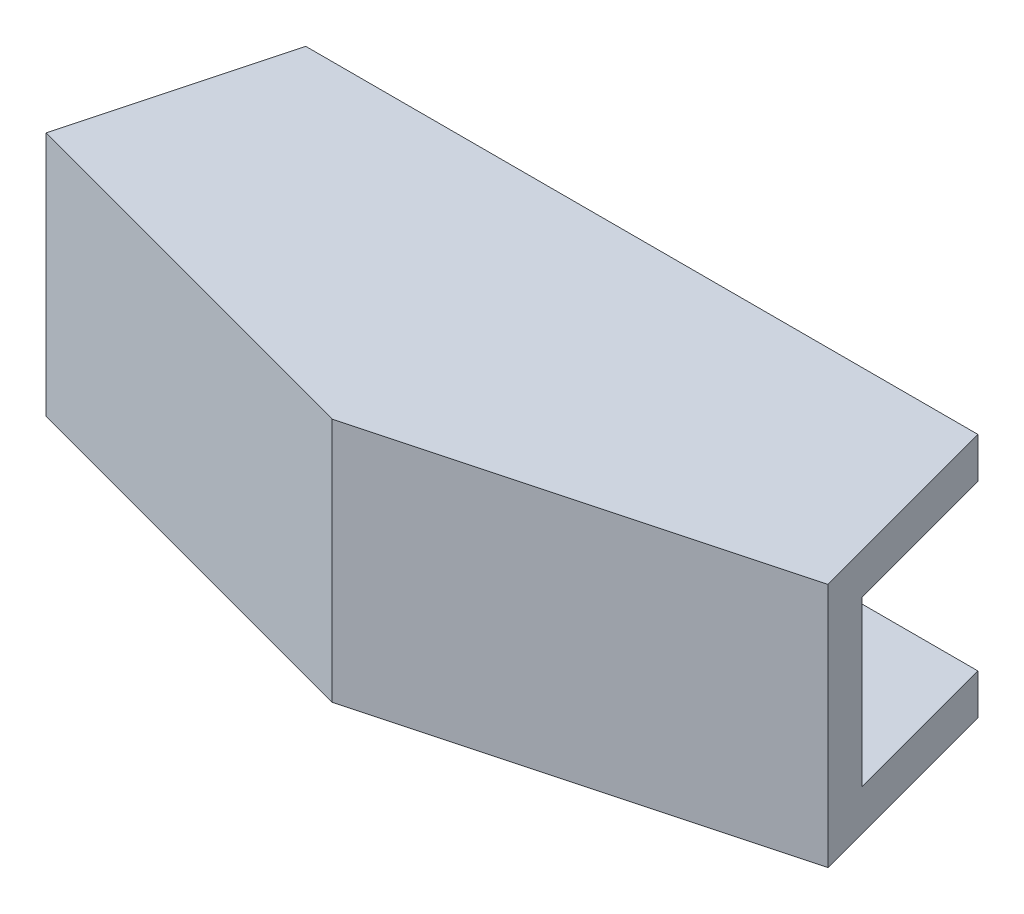
SolidWorks part; units mm, degrees
ref_plane "Front Plane" through (0, 0, 0) normal (0, 0, 1) x (1, 0, 0)
ref_plane "Top Plane" through (0, 0, 0) normal (0, 1, 0) x (1, 0, 0)
ref_plane "Right Plane" through (0, 0, 0) normal (1, 0, 0) x (0, 0, -1)
sketch "Base_Layout" plane through (0, 0, 0) normal (0, 1, 0) x (1, 0, 0)
  line L0 (-53.4672, -58.3773) -> (-53.4672, -18.3773) construction
  line L1 (-103.4672, -18.3773) -> (-3.4672, -18.3773) construction
  line L2 (-103.4672, -18.3773) -> (-103.4672, -58.3773) construction
  line L3 (-103.4672, -58.3773) -> (-3.4672, -58.3773) construction
  line L4 (-3.4672, -18.3773) -> (-3.4672, -58.3773) construction
  line L5 (-53.4672, -58.3773) -> (-24.4894, -50.6127) construction
  line L6 (-55.9672, -33.4014) -> (-50.9672, -33.4014) construction
  line L7 (-55.9672, -33.4014) -> (-55.9672, -58.3773) construction
  line L8 (-55.9672, -58.3773) -> (-50.9672, -58.3773) construction
  line L9 (-50.9672, -33.4014) -> (-50.9672, -58.3773) construction
  line L10 (-21.8056, -28.8775) -> (-16.5516, -48.4858) construction
  line L11 (-45.7132, -56.2996) -> (-16.5516, -48.4858) construction
  line L12 (-24.4894, -50.6127) -> (-24.4894, -58.3773) construction
  line L13 (-45.7132, -56.2996) -> (-50.9672, -36.6913) construction
  line L18 (-50.9672, -36.6913) -> (-21.8056, -28.8775) construction
  line L19 (-45.7132, -56.2996) -> (-44.1875, -61.9936)
  line L20 (-53.4672, -58.3773) -> (-53.4672, -68.287) construction
  line L21 (-53.4672, -64.4801) -> (2.0469, -49.6051)
  line L22 (-16.5516, -48.4858) -> (-15.0259, -54.1798)
  arc A0 (-38.9783, -54.495) -> (-38.4672, -58.3773) centre (-53.4672, -58.3773) cw construction
  point P22 (0, 0)
sketch "Sketch4" plane through (0, 0, 0) normal (0, 1, 0) x (1, 0, 0)
  line L0 (-53.4672, -64.4801) -> (-5.1709, -51.5391)
  line L1 (-53.4672, -37.3612) -> (-11.9506, -26.2369)
  line L2 (-5.1709, -51.5391) -> (-11.9506, -26.2369)
  line L3 (-53.4672, -18.3773) -> (-53.4672, -64.4801) construction
  line L4 (-53.4672, -58.3773) -> (-53.4672, -18.3773) construction
  line L5 (-50.9672, -36.6913) -> (-21.8056, -28.8775) construction
  line L6 (-103.4672, -18.3773) -> (-3.4672, -18.3773) construction
  line L7 (-101.7635, -51.5391) -> (-94.9838, -26.2369)
  line L8 (-53.4672, -37.3612) -> (-94.9838, -26.2369)
  line L9 (-53.4672, -64.4801) -> (-101.7635, -51.5391)
  point P5 (0, 0)
  point P6 (0, 0)
  point P12 (0, 0)
  point P17 (0, 0)
extrude "Boss-Extrude3" add sketch "Sketch4" along normal blind 5
sketch "Sketch5" plane through (0, 5, 0) normal (0, 1, 0) x (1, 0, 0)
  line L0 (-45.7132, -56.2996) -> (-6.6966, -45.8452)
  line L1 (-45.7132, -56.2996) -> (-16.5516, -48.4858) construction
  line L2 (-45.7132, -56.2996) -> (-50.9672, -36.6913)
  line L3 (-5.1709, -51.5391) -> (-11.9506, -26.2369) construction
  line L4 (-6.6966, -45.8452) -> (-5.1709, -51.5391)
  line L5 (-5.1709, -51.5391) -> (-53.4672, -64.4801)
  line L6 (-53.4672, -37.3612) -> (-50.9672, -36.6913)
  line L7 (-53.4672, -18.3773) -> (-53.4672, -68.287) construction
  line L8 (-53.4672, -37.3612) -> (-55.9672, -36.6913)
  line L9 (-101.7635, -51.5391) -> (-53.4672, -64.4801)
  line L10 (-100.2378, -45.8452) -> (-101.7635, -51.5391)
  line L11 (-61.2212, -56.2996) -> (-55.9672, -36.6913)
  line L12 (-61.2212, -56.2996) -> (-100.2378, -45.8452)
extrude "Boss-Extrude4" add sketch "Sketch5" along normal blind 20.3
sketch "Sketch6" plane through (0, 25.3, 0) normal (0, 1, 0) x (1, 0, 0)
  line L0 (-5.1709, -51.5391) -> (-11.9506, -26.2369)
  line L1 (-11.9506, -26.2369) -> (-53.4672, -37.3612)
  line L2 (-5.1709, -51.5391) -> (-53.4672, -64.4801)
  line L3 (-53.4672, -18.3773) -> (-53.4672, -68.287) construction
  line L4 (-101.7635, -51.5391) -> (-53.4672, -64.4801)
  line L5 (-94.9838, -26.2369) -> (-53.4672, -37.3612)
  line L6 (-101.7635, -51.5391) -> (-94.9838, -26.2369)
extrude "Boss-Extrude5" add sketch "Sketch6" along normal blind 5
sketch "Sketch7" plane through (0, 30.3, 0) normal (0, 1, 0) x (1, 0, 0)
  line L0 (-53.4672, -64.4801) -> (2.0469, -49.6051) construction
  line L1 (-94.9838, -26.2369) -> (-11.9506, -26.2369) construction
  line L2 (-94.9838, -26.2369) -> (-94.9838, -53.3558) construction
  line L3 (-94.9838, -53.3558) -> (-11.9506, -53.3558) construction
  line L4 (-11.9506, -26.2369) -> (-11.9506, -53.3558) construction
  line L5 (-53.4672, -64.4801) -> (-53.4672, -26.2369) construction
  point P10 (0, 0)
sketch "Sketch16" plane through (0, 30.3, 0) normal (0, 1, 0) x (1, 0, 0)
  line L0 (-53.4672, -64.4801) -> (-36.5375, -59.9438)
  line L1 (-53.4672, -64.4801) -> (-5.1709, -51.5391) construction
  line L2 (-53.4672, -64.4801) -> (-70.3969, -59.9438)
  line L3 (-101.7635, -51.5391) -> (-53.4672, -64.4801) construction
  line L4 (-36.5375, -59.9438) -> (-43.3172, -34.6415)
  line L5 (-11.9506, -26.2369) -> (-53.4672, -37.3612) construction
  line L6 (-70.3969, -59.9438) -> (-63.6172, -34.6415)
  line L7 (-53.4672, -37.3612) -> (-94.9838, -26.2369) construction
  line L8 (-43.3172, -56.584) -> (-63.6172, -56.584) construction
  line L9 (-43.3172, -34.6415) -> (-63.6172, -34.6415)
  line L11 (-53.4672, -64.4801) -> (-53.4672, -56.584) construction
  line L13 (-43.3172, -56.584) -> (-43.3172, -34.6415) construction
  line L14 (-63.6172, -56.584) -> (-63.6172, -34.6415) construction
  line L15 (-42.0231, -61.4137) -> (-43.3172, -56.584) construction
  line L16 (-63.6172, -56.584) -> (-64.9113, -61.4137) construction
sketch "Sketch20" plane through (0, 25.3, 0) normal (0, -1, 0) x (1, 0, 0)
  line L0 (-94.9838, 26.2369) -> (-11.9506, 26.2369)
  line L1 (-11.9506, 26.2369) -> (-53.4672, 37.3612)
  line L2 (-11.9506, 26.2369) -> (-50.9672, 36.6913) construction
  line L3 (-94.9838, 26.2369) -> (-53.4672, 37.3612)
  line L4 (-55.9672, 36.6913) -> (-94.9838, 26.2369) construction
  point P4 (0, 0)
extrude "Boss-Extrude16" add sketch "Sketch20" against normal blind 5
sketch "Sketch21" plane through (0, 0, 0) normal (0, -1, 0) x (1, 0, 0)
  line L0 (-11.9506, 26.2369) -> (-53.4672, 37.3612)
  line L1 (-53.4672, 37.3612) -> (-94.9838, 26.2369) construction
  line L2 (-11.9506, 26.2369) -> (-53.4672, 37.3612) construction
  line L3 (-53.4672, 37.3612) -> (-94.9838, 26.2369)
  line L4 (-94.9838, 26.2369) -> (-11.9506, 26.2369)
  point P10 (0, 0)
extrude "Boss-Extrude17" add sketch "Sketch21" against normal blind 5
